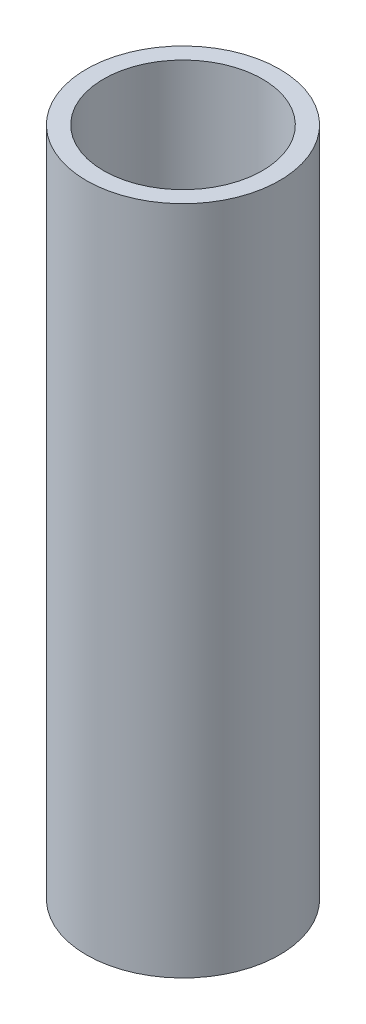
SolidWorks part; units mm, degrees
material "Thornel Mat VMA"
ref_plane "Front Plane" through (0, 0, 0) normal (0, 0, 1) x (1, 0, 0)
ref_plane "Top Plane" through (0, 0, 0) normal (0, 1, 0) x (1, 0, 0)
ref_plane "Right Plane" through (0, 0, 0) normal (1, 0, 0) x (0, 0, -1)
sketch "Sketch1" plane through (0, 0, 0) normal (0, 1, 0) x (1, 0, 0)
  circle A0 centre (0, 0) radius 7.9375
  circle A1 centre (0, 0) radius 9.652
  dimension "D1" = 15.875
  dimension "D2" = 19.304
extrude "Boss-Extrude1" add sketch "Sketch1" along normal blind 67
